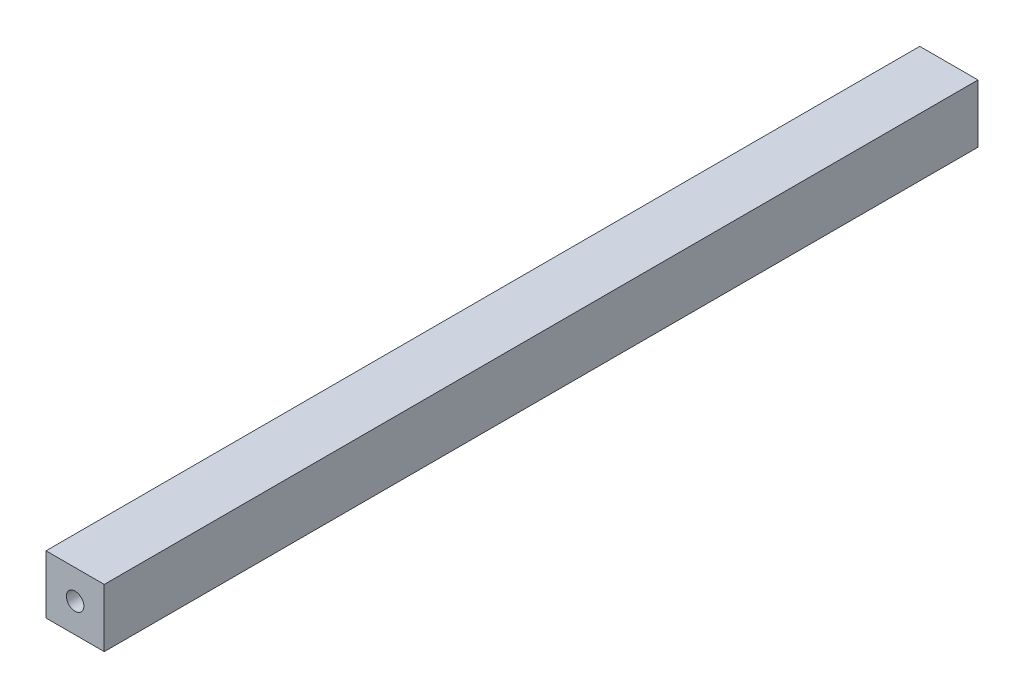
SolidWorks part; units mm, degrees
material "Alliage 1060"
ref_plane "Plan de face" through (0, 0, 0) normal (0, 0, 1) x (1, 0, 0)
ref_plane "Plan de dessus" through (0, 0, 0) normal (0, 1, 0) x (1, 0, 0)
ref_plane "Plan de droite" through (0, 0, 0) normal (1, 0, 0) x (0, 0, -1)
sketch "Esquisse1" plane through (0, 0, 0) normal (0, 0, 1) x (1, 0, 0)
  line L1 (-10, 10) -> (10, 10)
  line L2 (-10, 10) -> (-10, -10)
  line L3 (-10, -10) -> (10, -10)
  line L4 (10, 10) -> (10, -10)
  dimension "D1" = 20
  dimension "D2" = 20
  dimension "D3" = 10
  dimension "D4" = 10
extrude "Boss.-Extru.1" add sketch "Esquisse1" along normal blind 300
sketch "Esquisse2" plane through (0, 0, 300) normal (0, 0, 1) x (1, 0, 0)
  circle A0 centre (0, 0) radius 3
  dimension "D1" = 6
extrude "Enlèv. mat.-Extru.1" cut sketch "Esquisse2" against normal blind 200
sketch "Esquisse3" plane through (0, 0, 0) normal (0, 0, -1) x (-1, 0, 0)
  circle A0 centre (0, 0) radius 3
  dimension "D1" = 6
extrude "Enlèv. mat.-Extru.2" cut sketch "Esquisse3" against normal blind 200
